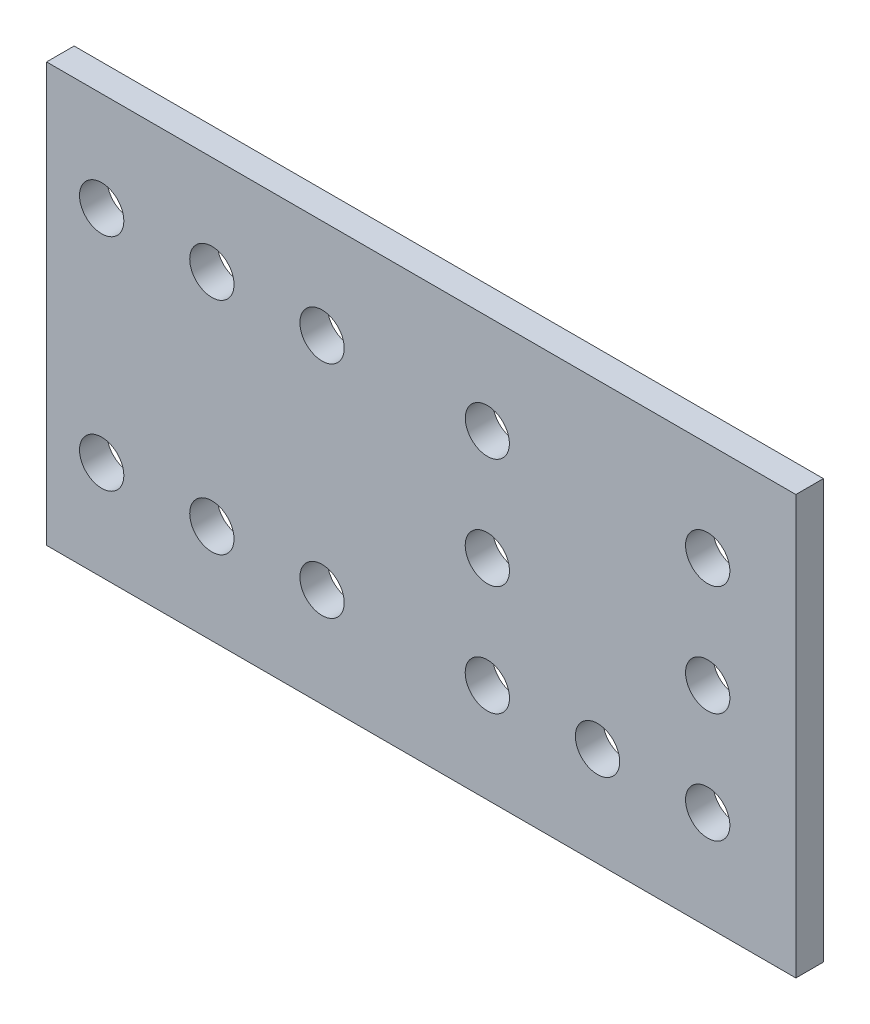
SolidWorks part; units mm, degrees
material "6061-T6 (SS)"
ref_plane "Front Plane" through (0, 0, 0) normal (0, 0, 1) x (1, 0, 0)
ref_plane "Top Plane" through (0, 0, 0) normal (0, 1, 0) x (1, 0, 0)
ref_plane "Right Plane" through (0, 0, 0) normal (1, 0, 0) x (0, 0, -1)
sketch "Sketch1" plane through (0, 0, 0) normal (0, 0, 1) x (1, 0, 0)
  line L1 (0, 0) -> (86.36, 0)
  line L2 (0, 0) -> (0, 48.26)
  line L3 (0, 48.26) -> (86.36, 48.26)
  line L4 (86.36, 0) -> (86.36, 48.26)
  dimension "D1" = 48.26
  dimension "D2" = 86.36
extrude "Boss-Extrude1" add sketch "Sketch1" along normal blind 3.175
sketch "Sketch2" plane through (0, 0, 3.175) normal (0, 0, 1) x (1, 0, 0)
  line L0 (0, 48.26) -> (0, 0) construction
  line L1 (0, 0) -> (86.36, 0) construction
  circle A0 centre (6.35, 36.83) radius 2.5527
  circle A1 centre (6.35, 11.43) radius 2.5527
  circle A2 centre (19.05, 36.83) radius 2.5527
  circle A3 centre (19.05, 11.43) radius 2.5527
  circle A4 centre (31.75, 36.83) radius 2.5527
  circle A5 centre (31.75, 11.43) radius 2.5527
  circle A6 centre (44.45, 36.83) radius 2.5527 construction
  circle A7 centre (44.45, 11.43) radius 2.5527 construction
  circle A8 centre (57.15, 36.83) radius 2.5527 construction
  circle A9 centre (57.15, 11.43) radius 2.5527 construction
  circle A10 centre (69.85, 36.83) radius 2.5527 construction
  circle A11 centre (69.85, 11.43) radius 2.5527 construction
  dimension "D1" = 5.1054
  dimension "D2" = 5.1054
  dimension "D3" = 25.4
  dimension "D4" = 6.35
  dimension "D5" = 11.43
  dimension "D6" = 6.35
  dimension "D8" = 12.7
  dimension "D7" = 6
extrude "Cut-Extrude1" cut sketch "Sketch2" against normal through all and the other way through all
sketch "Sketch3" plane through (0, 0, 0) normal (0, 0, -1) x (-1, 0, 0)
  line L1 (-86.36, 0) -> (-86.36, 48.26) construction
  line L2 (-86.36, 48.26) -> (0, 48.26) construction
  circle A0 centre (-76.2, 36.83) radius 2.5527
  circle A1 centre (-76.2, 24.13) radius 2.5527
  circle A2 centre (-50.8, 36.83) radius 2.54
  circle A3 centre (-50.8, 24.13) radius 2.5527
  dimension "D1" = 5.1054
  dimension "D2" = 5.1054
  dimension "D3" = 5.08
  dimension "D4" = 5.1054
  dimension "D5" = 10.16
  dimension "D6" = 10.16
  dimension "D7" = 25.4
  dimension "D8" = 25.4
  dimension "D9" = 11.43
  dimension "D10" = 11.43
  dimension "D11" = 24.13
  dimension "D12" = 24.13
extrude "Cut-Extrude2" cut sketch "Sketch3" against normal through all
sketch "Sketch4" plane through (0, 0, 0) normal (0, 0, -1) x (-1, 0, 0)
  line L1 (-86.36, 0) -> (-86.36, 48.26) construction
  line L2 (0, 0) -> (-86.36, 0) construction
  circle A0 centre (-76.2, 11.43) radius 2.5527
  circle A1 centre (-63.5, 11.43) radius 2.5527
  circle A2 centre (-50.8, 11.43) radius 2.5527
  dimension "D1" = 5.1054
  dimension "D2" = 11.43
  dimension "D3" = 10.16
  dimension "D5" = 12.7
  dimension "D4" = 3
extrude "Cut-Extrude3" cut sketch "Sketch4" against normal through all
